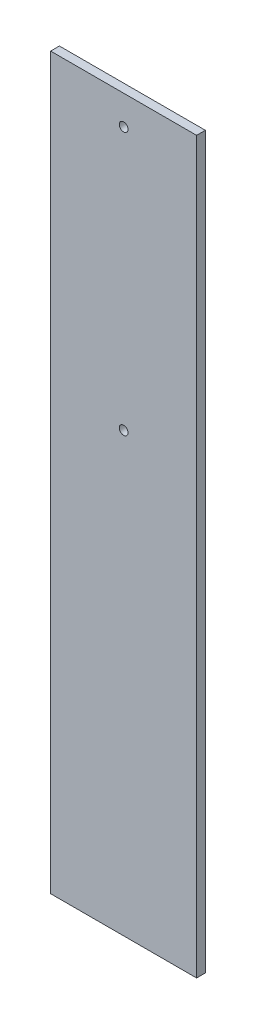
SolidWorks part; units mm, degrees
ref_plane "Front Plane" through (0, 0, 0) normal (0, 0, 1) x (1, 0, 0)
ref_plane "Top Plane" through (0, 0, 0) normal (0, 1, 0) x (1, 0, 0)
ref_plane "Right Plane" through (0, 0, 0) normal (1, 0, 0) x (0, 0, -1)
sketch "Sketch1" plane through (0, 0, 0) normal (0, 0, 1) x (1, 0, 0)
  line L1 (-25, 125) -> (25, 125)
  line L2 (-25, 125) -> (-25, -125)
  line L3 (-25, -125) -> (25, -125)
  line L4 (25, 125) -> (25, -125)
  line L5 (-25, 125) -> (25, -125) construction
  line L6 (-25, -125) -> (25, 125) construction
  circle A0 centre (0, 115) radius 1.5
  circle A1 centre (0, 25) radius 1.5
  point P0 (0, 0)
  point P9 (0, 125)
  dimension "D3" = 3
  dimension "D6" = 3
  dimension "D1" = 50
  dimension "D2" = 250
  dimension "D4" = 10
  dimension "D5" = 100
extrude "Boss-Extrude1" add sketch "Sketch1" along normal blind 3 contours L2 L3 L4 L1 | A0 | A1
